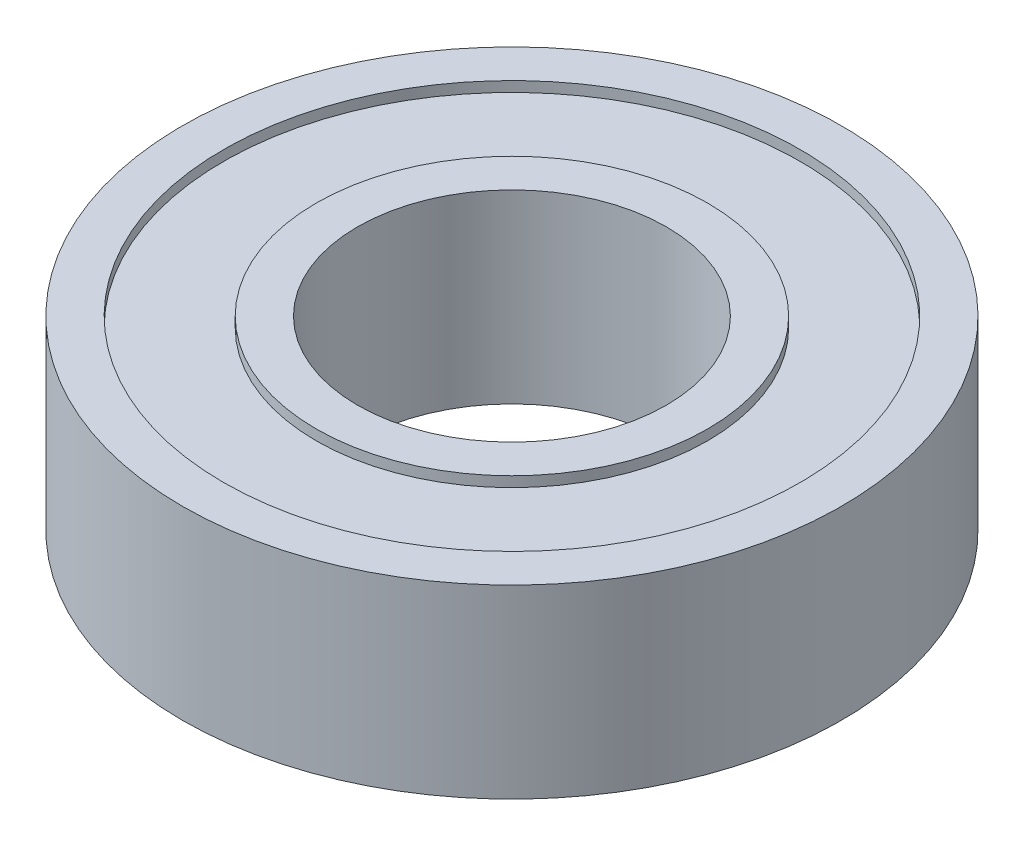
SolidWorks part; units mm, degrees
ref_plane "Plano frontal" through (0, 0, 0) normal (0, 0, 1) x (1, 0, 0)
ref_plane "Plano superior" through (0, 0, 0) normal (0, 1, 0) x (1, 0, 0)
ref_plane "Plano direito" through (0, 0, 0) normal (1, 0, 0) x (0, 0, -1)
sketch "Esboço1" plane through (0, 0, 0) normal (0, 0, 1) x (1, 0, 0)
  line L0 (0, 23.5028) -> (0, -15.3902) construction
  line L1 (7.5, -4.5) -> (9.5, -4.5)
  line L2 (7.5, -4.5) -> (7.5, 4.5)
  line L3 (7.5, 4.5) -> (9.5, 4.5)
  line L4 (9.5, -4.5) -> (9.5, 4.5)
  line L5 (14, 4.5) -> (16, 4.5)
  line L6 (14, 4.5) -> (14, -4.5)
  line L7 (14, -4.5) -> (16, -4.5)
  line L8 (16, 4.5) -> (16, -4.5)
  dimension "D1" = 7.5
  dimension "D2" = 16
  dimension "D3" = 2
  dimension "D4" = 2
  dimension "D5" = 9
  dimension "D6" = 4.5
revolve "Revolução1" add sketch "Esboço1" angle 360 about L0
sketch "Esboço2" plane through (0, 0, 0) normal (0, 0, 1) x (1, 0, 0)
  line L0 (-9.5, 4) -> (-14, 4)
  line L1 (-14, 4) -> (-14, -4)
  line L2 (-14, -4) -> (-9.5, -4)
  line L3 (-9.5, -4) -> (-9.5, 4)
  line L4 (14, 4.5) -> (-14, 4.5) construction
  line L5 (-14, -4.5) -> (14, -4.5) construction
  line L6 (0, 7.6203) -> (0, -8.3534) construction
  dimension "D1" = 9.5
  dimension "D2" = 14
  dimension "D3" = 0.5
  dimension "D4" = 0.5
revolve "Revolução2" add sketch "Esboço2" angle 360 about L6
